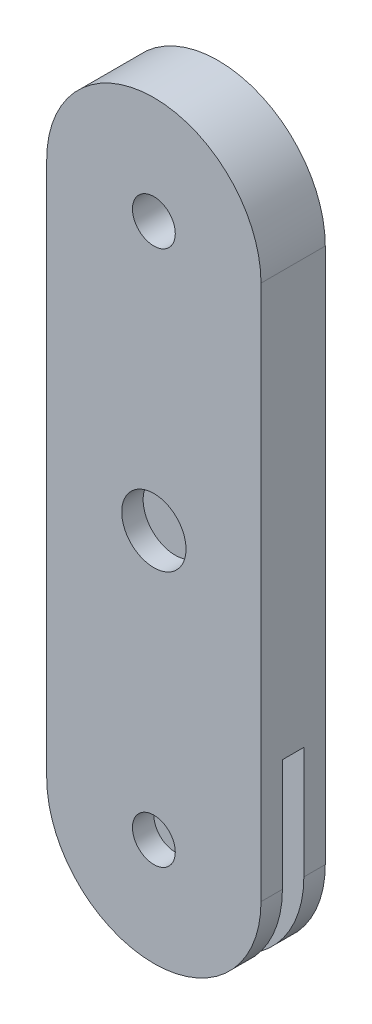
SolidWorks part; units mm, degrees
ref_plane "Plan de face" through (0, 0, 0) normal (0, 0, 1) x (1, 0, 0)
ref_plane "Plan de dessus" through (0, 0, 0) normal (0, 1, 0) x (1, 0, 0)
ref_plane "Plan de droite" through (0, 0, 0) normal (1, 0, 0) x (0, 0, -1)
sketch "Esquisse1" plane through (0, 0, 0) normal (0, 0, 1) x (1, 0, 0)
  line L0 (50, 0) -> (50, -250)
  line L2 (-50, -250) -> (-50, 0)
  arc A0 (50, 0) -> (-50, 0) centre (0, 0) ccw
  arc A1 (50, -250) -> (-50, -250) centre (0, -250) cw
extrude "Boss.-Extru.2" add sketch "Esquisse1" against normal mid plane 30
sketch "Esquisse2" plane through (0, 0, 0) normal (0, 0, 1) x (1, 0, 0)
  line L0 (44.95, -184.3425) -> (44.95, -56.8828)
  line L2 (34.95, -46.8828) -> (-34.95, -46.8828)
  line L3 (-44.95, -184.3425) -> (-44.95, -56.8828)
  line L4 (50, -250) -> (50, 0) construction
  line L5 (50, -198.501) -> (50, -250)
  line L7 (-50, 0) -> (-50, -250) construction
  line L8 (-50, -198.501) -> (-50, -250)
  line L9 (-54.1148, -201.1531) -> (-50, -198.501)
  line L10 (54.1148, -201.1531) -> (50, -198.501)
  arc A0 (44.95, -56.8828) -> (34.95, -46.8828) centre (34.95, -56.8828) ccw
  arc A1 (54.1148, -201.1531) -> (44.95, -184.3425) centre (64.95, -184.3425) cw
  arc A2 (-54.1148, -201.1531) -> (-44.95, -184.3425) centre (-64.95, -184.3425) ccw
  arc A3 (-44.95, -56.8828) -> (-34.95, -46.8828) centre (-34.95, -56.8828) cw
  arc A10 (50, -250) -> (-50, -250) centre (0, -250) cw
  arc A11 (-50, -250) -> (50, -250) centre (0, -250) ccw construction
  dimension "D1" = 10
  dimension "D2" = 20
extrude "Enlèv. mat.-Extru.1" cut sketch "Esquisse2" against normal mid plane 10
sketch "Esquisse3" plane through (0, 0, 15) normal (0, 0, 1) x (1, 0, 0)
  circle A0 centre (0, 0) radius 10
extrude "Enlèv. mat.-Extru.2" cut sketch "Esquisse3" against normal through all
sketch "Esquisse4" plane through (0, 0, -5) normal (0, 0, 1) x (1, 0, 0)
  circle A0 centre (0, -250) radius 10
sketch "Esquisse5" plane through (0, 0, 15) normal (0, 0, 1) x (1, 0, 0)
  circle A1 centre (0, -125) radius 15
  dimension "D1" = 125
extrude "Enlèv. mat.-Extru.3" cut sketch "Esquisse5" against normal blind 15
extrude "Enlèv. mat.-Extru.4" cut sketch "Esquisse4" against normal through all and the other way blind 210
